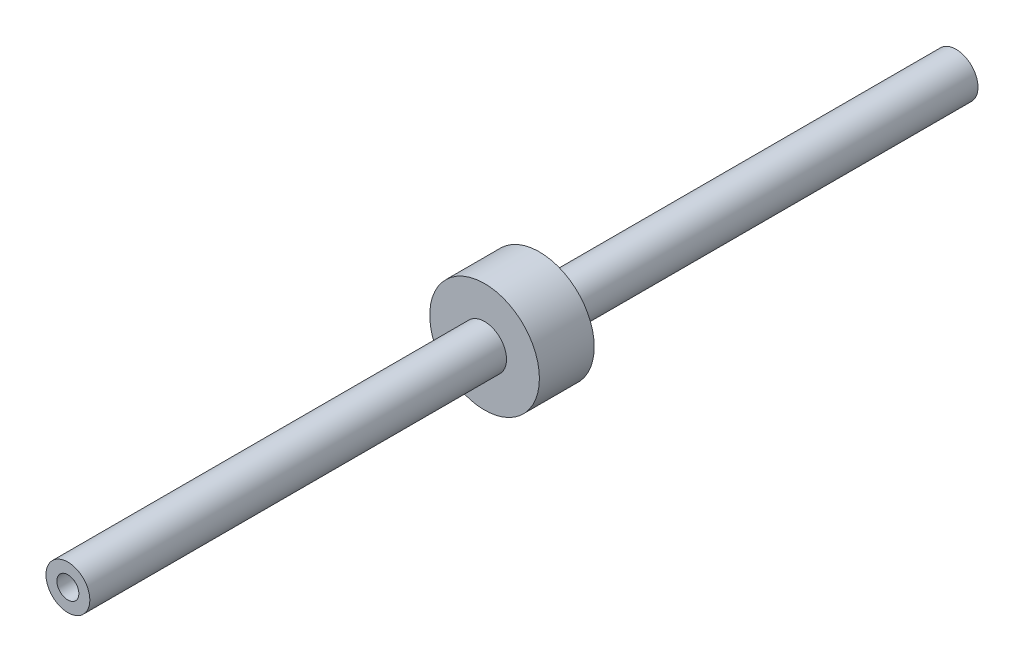
SolidWorks part; units mm, degrees
ref_plane "Front Plane" through (0, 0, 0) normal (0, 0, 1) x (1, 0, 0)
ref_plane "Top Plane" through (0, 0, 0) normal (0, 1, 0) x (1, 0, 0)
ref_plane "Right Plane" through (0, 0, 0) normal (1, 0, 0) x (0, 0, -1)
sketch "Sketch1" plane through (0, 0, 0) normal (0, 0, 1) x (1, 0, 0)
  circle A0 centre (0, 0) radius 2
extrude "Boss-Extrude1" add sketch "Sketch1" along normal blind 38
sketch "Sketch2" plane through (0, 0, 38) normal (0, 0, 1) x (1, 0, 0)
  circle A0 centre (0, 0) radius 5
extrude "Boss-Extrude2" add sketch "Sketch2" along normal blind 5
sketch "Sketch3" plane through (0, 0, 43) normal (0, 0, 1) x (1, 0, 0)
  circle A0 centre (0, 0) radius 2
extrude "Boss-Extrude3" add sketch "Sketch3" along normal blind 38
sketch "Sketch4" plane through (0, 0, 0) normal (0, 0, -1) x (-1, 0, 0)
  circle A0 centre (0, 0) radius 1
extrude "Cut-Extrude1" cut sketch "Sketch4" against normal blind 5
sketch "Sketch5" plane through (0, 0, 81) normal (0, 0, 1) x (1, 0, 0)
  circle A0 centre (0, 0) radius 1
extrude "Cut-Extrude2" cut sketch "Sketch5" against normal blind 5 and the other way through all
